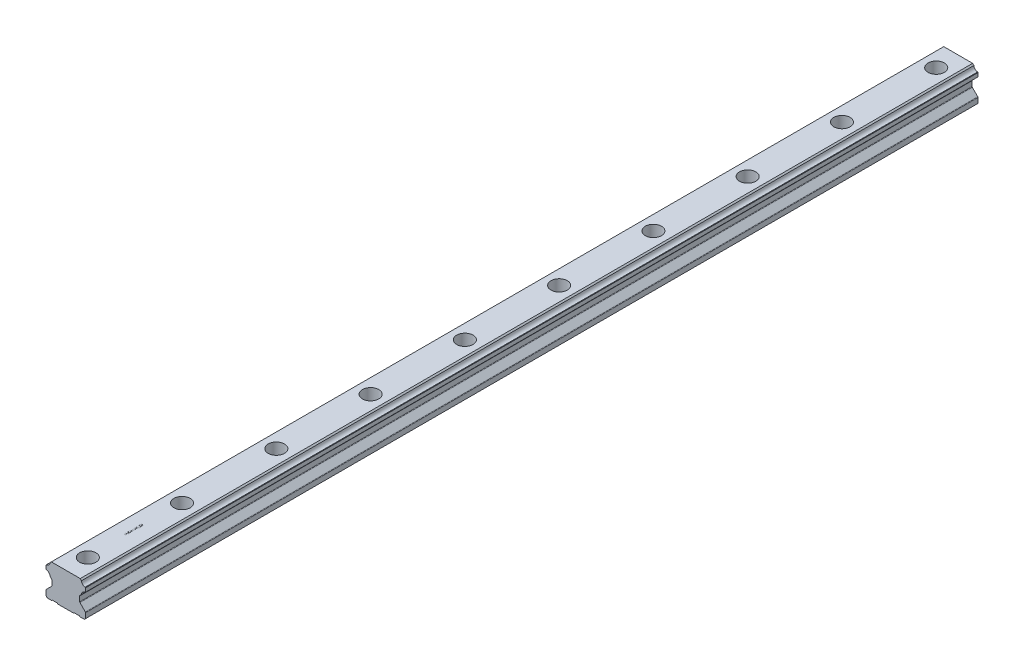
SolidWorks part; units mm, degrees
material "镀铬不锈钢"
ref_plane "前视基准面" through (0, 0, 0) normal (0, 0, 1) x (1, 0, 0)
ref_plane "上视基准面" through (0, 0, 0) normal (0, 1, 0) x (1, 0, 0)
ref_plane "右视基准面" through (0, 0, 0) normal (1, 0, 0) x (0, 0, -1)
sketch "草图1" plane through (0, 0, 0) normal (0, 0, 1) x (1, 0, 0)
  line L28 (-23, 53) -> (-24.9911, 51.0089)
  line L29 (31.0607, 11.0808) -> (22.5393, 19.6021)
  line L30 (-31.5, 10.0201) -> (-31.5, 2)
  line L31 (-13.5, 1) -> (-12.5, 0)
  line L32 (30.8759, 37.8759) -> (31.5, 38.5)
  line L33 (-22.1, 28.4787) -> (-22.1, 20.6627)
  line L34 (23, 53) -> (-23, 53)
  line L35 (-31.5, 38.5) -> (-30.8759, 37.8759)
  line L36 (31.5, 2) -> (31.5, 10.0201)
  line L37 (31.5, 38.5) -> (31.5, 44.5)
  line L38 (31.5, 44.5) -> (30.8749, 45.1251)
  line L39 (-31.5, 44.5) -> (-31.5, 38.5)
  line L40 (-24.9911, 31.9911) -> (-22.5393, 29.5393)
  line L41 (24.9911, 51.0089) -> (23, 53)
  line L42 (-22.5, 0) -> (-21.5, 1)
  line L43 (22.1, 20.6627) -> (22.1, 28.4787)
  line L44 (-30.8749, 45.1251) -> (-31.5, 44.5)
  line L45 (13.5, 1) -> (21.5, 1)
  line L46 (-12.5, 0) -> (12.5, 0)
  line L47 (-31.5, 2) -> (-29.5, 0)
  line L48 (22.5, 0) -> (29.5, 0)
  line L49 (-29.5, 0) -> (-22.5, 0)
  line L50 (29.5, 0) -> (31.5, 2)
  line L51 (12.5, 0) -> (13.5, 1)
  line L52 (22.5393, 29.5393) -> (24.9911, 31.9911)
  line L53 (-22.5393, 19.6021) -> (-31.0607, 11.0808)
  line L54 (21.5, 1) -> (22.5, 0)
  line L55 (-21.5, 1) -> (-13.5, 1)
  arc A10 (-31.0607, 11.0808) -> (-31.5, 10.0201) centre (-30, 10.0201) ccw
  arc A11 (-22.1, 28.4787) -> (-22.5393, 29.5393) centre (-23.6, 28.4787) ccw
  arc A12 (22.1, 20.6627) -> (22.5393, 19.6021) centre (23.6, 20.6627) ccw
  arc A13 (30.8759, 37.8759) -> (24.9911, 31.9911) centre (30.99, 31.877) ccw
  arc A14 (-30.8749, 45.1251) -> (-24.9911, 51.0089) centre (-30.99, 51.124) ccw
  arc A15 (31.5, 10.0201) -> (31.0607, 11.0808) centre (30, 10.0201) ccw
  arc A16 (22.5393, 29.5393) -> (22.1, 28.4787) centre (23.6, 28.4787) ccw
  arc A17 (-24.9911, 31.9911) -> (-30.8759, 37.8759) centre (-30.99, 31.877) ccw
  arc A18 (24.9911, 51.0089) -> (30.8749, 45.1251) centre (30.99, 51.124) ccw
  arc A19 (-22.5393, 19.6021) -> (-22.1, 20.6627) centre (-23.6, 20.6627) ccw
extrude "凸台-拉伸1" add sketch "草图1" against normal blind 1420
hole_wizard "M16 六角凹头螺钉的柱形沉头孔1" positions "草图3" profile "草图2" counterbore size "M16" standard "ISO" end condition through all
sketch "草图3" plane through (-6.8239, 53, -130.7788) normal (0, 1, 0) x (-1, 0, 0)
  point P0 (-6.8239, 95.7788)
  dimension "D1" = 35
sketch "草图2" plane through (0, 53, -35) normal (1, 0, 0) x (0, 0, 1)
  line L0 (0, 0) -> (0, 53)
  line L1 (0, 53) -> (9, 53)
  line L3 (9, 53) -> (9, 22)
  line L4 (9, 22) -> (13, 22)
  line L5 (13, 22) -> (13, 0)
  line L7 (13, 0) -> (0, 0)
  line L11 (0, -6.35) -> (0, 107.95) construction
  dimension "通孔孔直径" = 18
  dimension "通孔孔深度" = 53
  dimension "柱形沉头孔直径" = 26
  dimension "柱形沉头孔深度" = 22
pattern_linear "阵列(线性)1" count 10 spacing 150 along (0, 0, -1) of "M16 六角凹头螺钉的柱形沉头孔1"
sketch "草图6" plane through (0, 53, 0) normal (0, 1, 0) x (1, 0, 0)
  line L0 (0, 35) -> (0, 185) construction
  text T0 "HIWIN HG65"
extrude "切除-拉伸1" cut sketch "草图6" against normal blind 0.1
equation "\"D1@凸台-拉伸1\" = 2 * \"D1@草图3\" + \"D3@阵列(线性)1\" *  ( \"D1@阵列(线性)1\"  - 1) "
